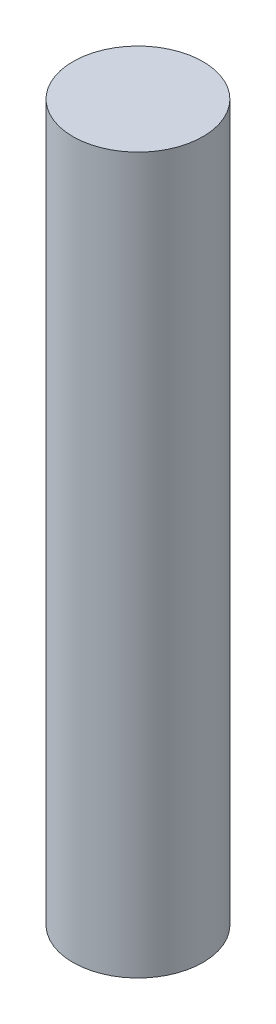
SolidWorks part; units mm, degrees
ref_plane "Alzado" through (0, 0, 0) normal (0, 0, 1) x (1, 0, 0)
ref_plane "Planta" through (0, 0, 0) normal (0, 1, 0) x (1, 0, 0)
ref_plane "Vista lateral" through (0, 0, 0) normal (1, 0, 0) x (0, 0, -1)
sketch "Croquis1" plane through (0, 0, 0) normal (0, 1, 0) x (1, 0, 0)
  circle A0 centre (0, 0) radius 100
  dimension "D1" = 200
extrude "Saliente-Extruir1" add sketch "Croquis1" along normal blind 1100
